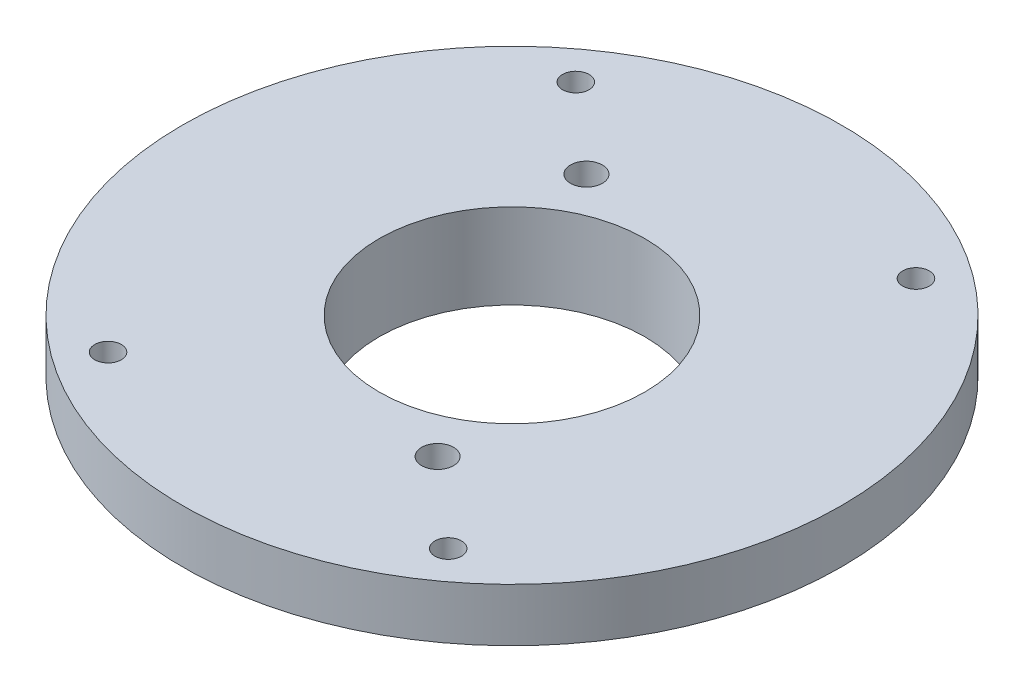
SolidWorks part; units mm, degrees
material "Delrin 2700 NC010, copolymère d'acétal à faible viscosité (SS)"
ref_plane "Plan de face" through (0, 0, 0) normal (0, 0, 1) x (1, 0, 0)
ref_plane "Plan de dessus" through (0, 0, 0) normal (0, 1, 0) x (1, 0, 0)
ref_plane "Plan de droite" through (0, 0, 0) normal (1, 0, 0) x (0, 0, -1)
sketch "Esquisse1" plane through (0, 0, 0) normal (0, 0, 1) x (1, 0, 0)
  line L0 (-12.5, 8) -> (-31, 8)
  line L1 (-31, 8) -> (-31, 3)
  line L2 (-31, 3) -> (-22.5, 3)
  line L3 (-22.5, 3) -> (-22.5, 0)
  line L4 (-22.5, 0) -> (-12.5, 0)
  line L5 (-12.5, 0) -> (-12.5, 7.9139)
  line L6 (0, 10) -> (0, -10) construction
  line L7 (-12.5, 8) -> (-12.5, 7.9139)
revolve "Révolution1" add sketch "Esquisse1" angle 360 about L6
sketch "Esquisse2" plane through (0, 8, 0) normal (0, 1, 0) x (1, 0, 0)
  line L0 (-40, 0) -> (40, 0) construction
  circle A0 centre (-16, 22) radius 1.25
  circle A1 centre (16, 22) radius 1.25
  circle A2 centre (16, -22) radius 1.25
  circle A3 centre (-16, -22) radius 1.25
  circle A4 centre (-8, 15) radius 1.5
  circle A5 centre (8, -15) radius 1.5
  dimension "D1" = 17
  dimension "D4" = 15
  dimension "D2" = 17
  dimension "D3" = 180
extrude "Enlèv. mat.-Extru.1" cut sketch "Esquisse2" against normal blind 8
